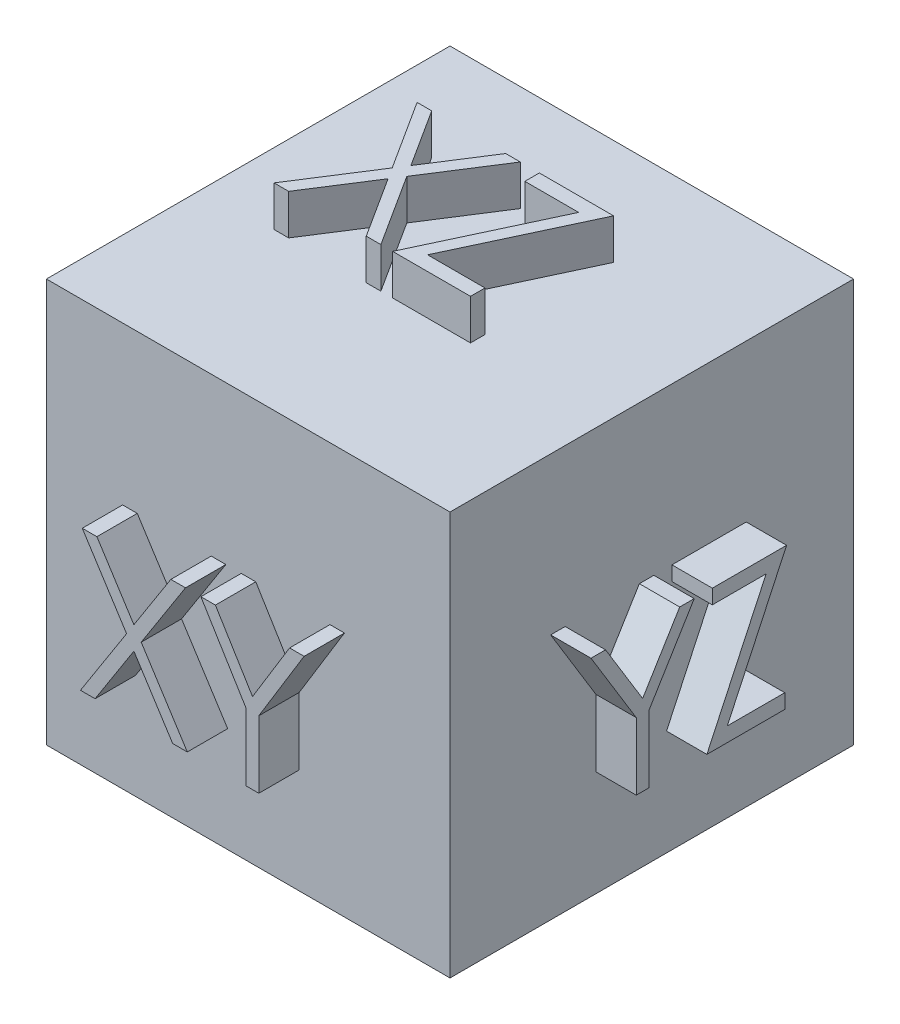
SolidWorks part; units mm, degrees
ref_plane "Front Plane" through (0, 0, 0) normal (0, 0, 1) x (1, 0, 0)
ref_plane "Top Plane" through (0, 0, 0) normal (0, 1, 0) x (1, 0, 0)
ref_plane "Right Plane" through (0, 0, 0) normal (1, 0, 0) x (0, 0, -1)
sketch "Sketch1" plane through (0, 0, 0) normal (0, 1, 0) x (1, 0, 0)
  line L1 (0, 0) -> (10, 0)
  line L2 (0, 0) -> (0, 10)
  line L3 (0, 10) -> (10, 10)
  line L4 (10, 0) -> (10, 10)
  dimension "D1" = 10
  dimension "D2" = 10
extrude "Boss-Extrude1" add sketch "Sketch1" along normal blind 10
sketch "Sketch2" plane through (0, 0, 0) normal (0, 0, 1) x (1, 0, 0)
  text T0 "XY\r\n"
extrude "Boss-Extrude2" add sketch "Sketch2" along normal blind 1
sketch "Sketch3" plane through (0, 10, 0) normal (0, 1, 0) x (1, 0, 0)
  text T0 "XZ\r\n"
extrude "Boss-Extrude3" add sketch "Sketch3" along normal blind 1
sketch "Sketch4" plane through (10, 0, 0) normal (1, 0, 0) x (0, 0, -1)
  text T0 "YZ\r\n"
extrude "Boss-Extrude4" add sketch "Sketch4" along normal blind 1
